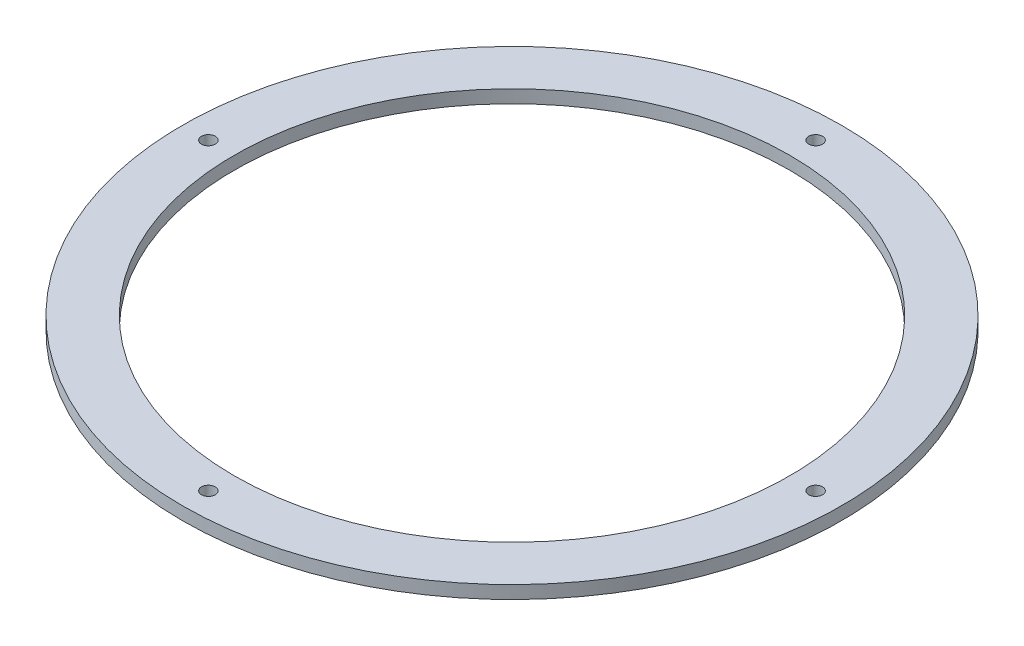
SolidWorks part; units mm, degrees
material "Pine"
ref_plane "Front Plane" through (0, 0, 0) normal (0, 0, 1) x (1, 0, 0)
ref_plane "Top Plane" through (0, 0, 0) normal (0, 1, 0) x (1, 0, 0)
ref_plane "Right Plane" through (0, 0, 0) normal (1, 0, 0) x (0, 0, -1)
sketch "Sketch1" plane through (0, 0, 0) normal (0, 1, 0) x (1, 0, 0)
  circle A0 centre (0, 0) radius 161.4
  circle A1 centre (0, 0) radius 136
  dimension "D1" = 25.4
  dimension "D2" = 272
extrude "Boss-Extrude1" add sketch "Sketch1" along normal blind 6.35
sketch "Sketch2" plane through (0, 6.35, 0) normal (0, 1, 0) x (1, 0, 0)
  line L0 (0, 0) -> (0, -161.4) construction
  circle A0 centre (0, 0) radius 161.4 construction
  point P6 (0, -148.7)
  dimension "D1" = 12.7
hole_wizard "1/4 Clearance Hole1" positions "Sketch2" profile "Sketch3" hole size "1/4" standard "ANSI Inch" end condition through all
sketch "Sketch3" plane through (0, 6.35, 148.7) normal (1, 0, 0) x (0, 0, 1)
  line L0 (0, 0) -> (0, 6.35)
  line L1 (0, 6.35) -> (3.3782, 6.35)
  line L2 (3.3782, 6.35) -> (3.3782, 0)
  line L5 (3.3782, 0) -> (0, 0)
  line L11 (0, -6.35) -> (0, 107.95) construction
  dimension "Thru Hole Dia." = 6.7564
  dimension "Thru Hole Depth" = 6.35
pattern_circular "CirPattern1" count 4 every 90 about axis through (0, 0, 0) along (0, 1, 0) of "1/4 Clearance Hole1"
